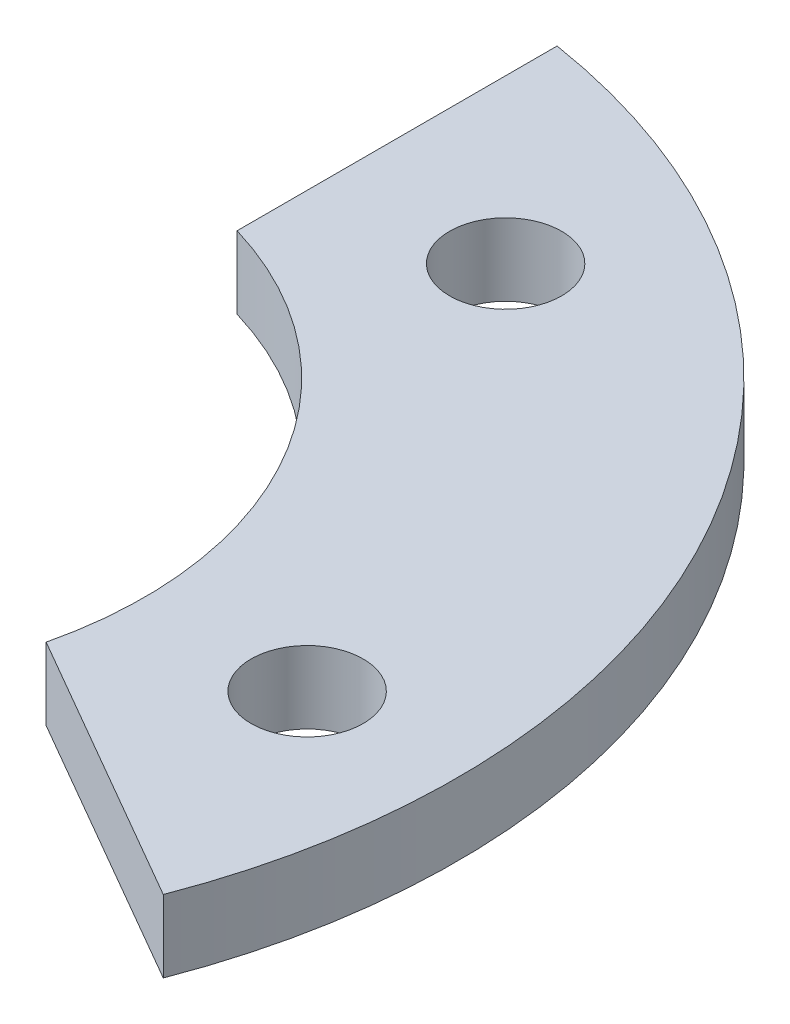
SolidWorks part; units mm, degrees
material "Balsa"
ref_plane "Front Plane" through (0, 0, 0) normal (0, 0, 1) x (1, 0, 0)
ref_plane "Top Plane" through (0, 0, 0) normal (0, 1, 0) x (1, 0, 0)
ref_plane "Right Plane" through (0, 0, 0) normal (1, 0, 0) x (0, 0, -1)
sketch "Sketch1" plane through (0, 0, 0) normal (0, 1, 0) x (1, 0, 0)
  line L0 (-38.3, 0) -> (38.3, 0) construction
  line L1 (0, 38.3) -> (0, -38.3) construction
  circle A0 centre (0, 0) radius 38.3
  circle A1 centre (30, 0) radius 3.1
  circle A2 centre (0, 0) radius 21
  circle A3 centre (15, -25.9808) radius 3.1
  circle A4 centre (-15, -25.9808) radius 3.1
  circle A5 centre (-30, 0) radius 3.1
  circle A6 centre (-15, 25.9808) radius 3.1
  circle A7 centre (15, 25.9808) radius 3.1
  point P23 (0, 0)
  dimension "D1" = 42
  dimension "D2" = 76.6
  dimension "D3" = 6.2
  dimension "D4" = 30
  dimension "D5" = 6
extrude "Boss-Extrude1" add sketch "Sketch1" along normal blind 4
sketch "Sketch2" plane through (0, 4, 0) normal (0, 1, 0) x (1, 0, 0)
  line L0 (0, 0) -> (0, 45.284) construction
  line L1 (0, 0) -> (52.3716, -30.2368) construction
  line L2 (6, 50.2763) -> (6, 14.2975)
  line L3 (15.382, -1.9526) -> (46.5406, -19.942)
  arc A0 (15.382, -1.9526) -> (6, 14.2975) centre (0, 0) ccw
  arc A2 (6, 50.2763) -> (46.5406, -19.942) centre (0, 0) ccw
  dimension "D1" = 120
  dimension "D2" = 6
  dimension "D3" = 6
extrude "Cut-Extrude1" cut sketch "Sketch2" against normal blind 10 contours L2 A0 L3 A2
